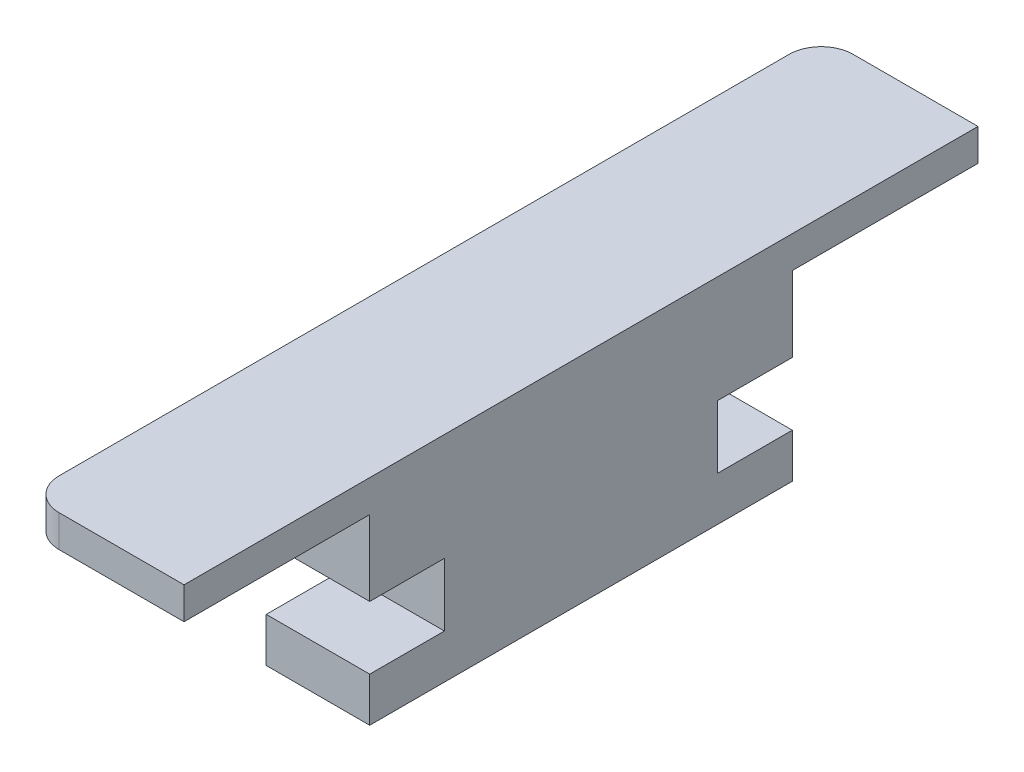
SolidWorks part; units mm, degrees
ref_plane "Front Plane" through (0, 0, 0) normal (0, 0, 1) x (1, 0, 0)
ref_plane "Top Plane" through (0, 0, 0) normal (0, 1, 0) x (1, 0, 0)
ref_plane "Right Plane" through (0, 0, 0) normal (1, 0, 0) x (0, 0, -1)
sketch "Sketch1" plane through (0, 0, 0) normal (0, 1, 0) x (1, 0, 0)
  line L0 (1.0057, -6.715) -> (1.0057, 13.085)
  line L1 (1.0057, 13.085) -> (75.8057, 13.085)
  line L2 (1.0057, -6.715) -> (10.7057, -6.715)
  line L3 (10.7057, -6.715) -> (10.7057, 7.685)
  line L4 (10.7057, -13.515) -> (10.7057, 7.685)
  line L5 (30.7855, -6.715) -> (75.8057, -6.715)
  line L6 (75.8057, -6.715) -> (75.8057, 13.085)
  arc A0 (30.7855, -6.715) -> (10.7057, 7.685) centre (10.7057, -13.515) ccw
  arc A1 (10.7057, 7.685) -> (33.7057, -6.715) centre (10.7057, -17.8831) cw
  arc A2 (10.7057, 7.685) -> (33.7057, -6.715) centre (13.0157, -14.1934) cw
  dimension "D2" = 21.2
  dimension "D1" = 9.7
  dimension "D3" = 19.8
  dimension "D4" = 74.8
  dimension "D5" = 14.4
  dimension "D6" = 19.8
  dimension "D7" = 23
extrude "Boss-Extrude1" add sketch "Sketch1" along normal blind 15.3 contours A0 L5 L6 L1 L0 L2 L3
sketch "Sketch4" plane through (75.8057, 0, 0) normal (1, 0, 0) x (0, 0, -1)
  line L0 (-6.715, 4.35) -> (0.285, 4.35)
  line L1 (-6.715, 15.3) -> (-6.715, 0) construction
  line L2 (0.285, 4.35) -> (0.285, 10.25)
  line L3 (0.285, 10.25) -> (-6.715, 10.25)
  line L4 (-6.715, 10.25) -> (-6.715, 4.35)
  line L5 (-6.715, 0) -> (13.085, 0) construction
  dimension "D1" = 7
  dimension "D2" = 5.9
  dimension "D3" = 4.35
extrude "Cut-Extrude1" cut sketch "Sketch4" against normal through all
sketch "Sketch5" plane through (0, 15.3, 0) normal (0, 1, 0) x (1, 0, 0)
  line L1 (1.0057, 13.085) -> (75.8057, 13.085)
  line L2 (1.0057, 13.085) -> (1.0057, -6.715)
  line L3 (1.0057, -6.715) -> (75.8057, -6.715)
  line L4 (75.8057, 13.085) -> (75.8057, -6.715)
extrude "Boss-Extrude2" add sketch "Sketch5" along normal blind 2
sketch "Sketch6" plane through (0, 0, -13.085) normal (0, 0, -1) x (-1, 0, 0)
  line L0 (-75.8057, 17.3) -> (-75.8057, 20.3)
  line L1 (-1.0057, 17.3) -> (-1.0057, 20.3)
  line L2 (-1.0057, 20.3) -> (-75.8057, 20.3)
  line L3 (-75.8057, 17.3) -> (-1.0057, 17.3)
  dimension "D1" = 3
extrude "Boss-Extrude3" add sketch "Sketch6" against normal blind 37.2
sketch "Sketch7" plane through (1.0057, 0, 0) normal (-1, 0, 0) x (0, 0, 1)
  line L1 (24.115, 17.3) -> (-13.085, 17.3)
  line L2 (24.115, 17.3) -> (24.115, 20.3)
  line L3 (24.115, 20.3) -> (-13.085, 20.3)
  line L4 (-13.085, 17.3) -> (-13.085, 20.3)
extrude "Boss-Extrude4" add sketch "Sketch7" along normal blind 5
fillet "Fillet1" radius 3 1 edges at (-3.9943, 18.8, 24.115)
sketch "Sketch8" plane through (0, 20.3, 0) normal (0, 1, 0) x (1, 0, 0)
  line L0 (75.8057, 13.085) -> (90.8057, 13.085)
  line L1 (90.8057, 13.085) -> (90.8057, -3.0727)
  line L2 (75.8057, 13.085) -> (75.8057, -24.115)
  arc A0 (90.8057, -3.0727) -> (75.8057, -24.115) centre (68.5463, -3.0727) cw
  dimension "D1" = 15
  dimension "D2" = 16.1576
extrude "Boss-Extrude5" add sketch "Sketch8" against normal blind 23.3
fillet "Fillet2" radius 2 2 edges at (90.8057, -3, -5.0062) (86.6718, -3, 15.9934)
sketch "Sketch10" plane through (0, 0, 0) normal (0, -1, 0) x (-1, 0, 0)
  line L1 (-1.0057, -6.715) -> (-75.8057, -6.715)
  line L2 (-1.0057, -6.715) -> (-1.0057, 13.085)
  line L3 (-1.0057, 13.085) -> (-75.8057, 13.085)
  line L4 (-75.8057, -6.715) -> (-75.8057, 13.085)
extrude "Cut-Extrude2" cut sketch "Sketch10" against normal blind 0.2
sketch "Sketch11" plane through (0, -3, 0) normal (0, -1, 0) x (-1, 0, 0)
  line L0 (-75.8057, 13.085) -> (-75.8057, 3.085)
  line L1 (-75.8057, 13.085) -> (-75.8057, -21.9868) construction
  line L2 (-75.8057, 13.085) -> (-83.3057, 13.085)
  line L3 (-88.8057, 13.085) -> (-75.8057, 13.085) construction
  line L4 (-83.3057, 13.085) -> (-83.3057, 8.085)
  arc A1 (-75.8057, 3.085) -> (-83.3057, 8.085) centre (-75.8057, 11.21) cw
  dimension "D1" = 10
  dimension "D2" = 7.5
  dimension "D3" = 5
extrude "Cut-Extrude3" cut sketch "Sketch11" against normal blind 5 draft 30 draft outward yes
sketch "Sketch14" plane through (0, 0, -13.085) normal (0, 0, -1) x (-1, 0, 0)
  line L0 (-72.9189, 2) -> (-73.9582, 0.2)
  line L1 (-73.9582, 0.2) -> (-75.8057, 0.2)
  line L2 (-75.8057, 0.2) -> (-75.8057, 2)
  line L3 (-86.1924, 2) -> (-72.9189, 2) construction
  line L4 (-75.8057, 2) -> (-72.9189, 2)
extrude "Boss-Extrude6" add sketch "Sketch14" against normal blind 15
mirror "Mirror1" about plane through (0, 15.3, -13.085) normal (0, 0, -1) of bodies 111
sketch "Sketch15" plane through (90.8057, 0, 0) normal (1, 0, 0) x (0, 0, -1)
  line L1 (-30.8059, 31.1563) -> (61.6184, 31.1563)
  line L2 (-30.8059, 31.1563) -> (-30.8059, -15.5058)
  line L3 (-30.8059, -15.5058) -> (61.6184, -15.5058)
  line L4 (61.6184, 31.1563) -> (61.6184, -15.5058)
extrude "Cut-Extrude4" cut sketch "Sketch15" against normal up to surface (80.1 mm away)
